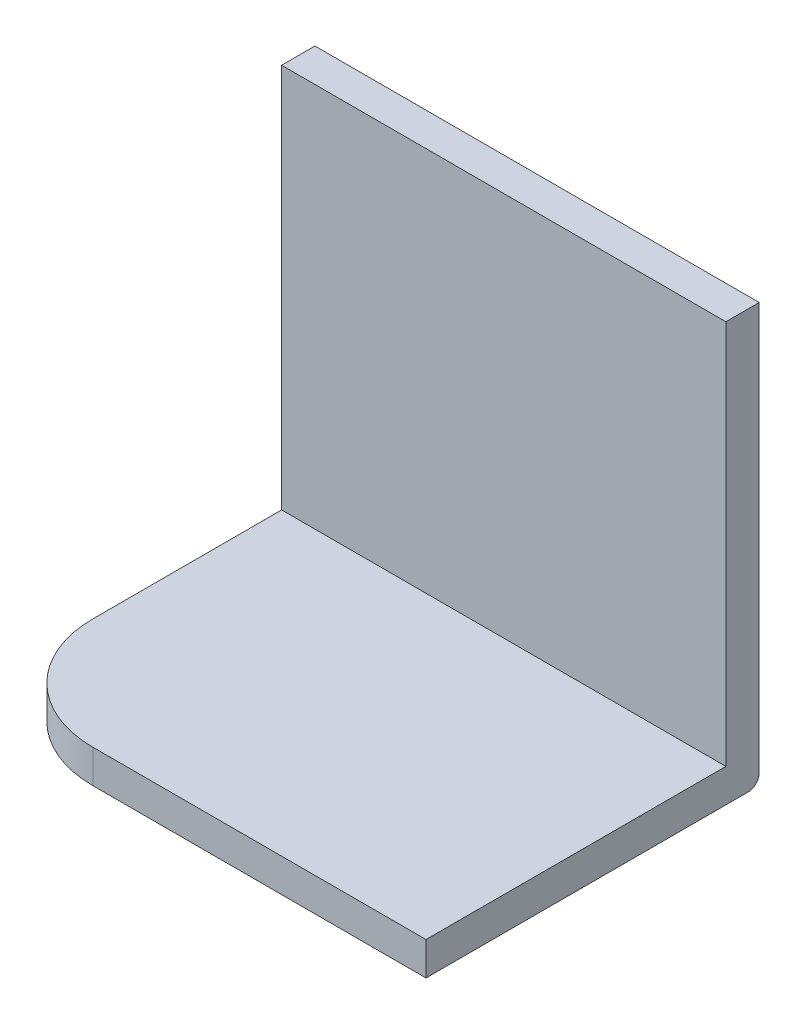
SolidWorks part; units mm, degrees
ref_plane "前视基准面" through (0, 0, 0) normal (0, 0, 1) x (1, 0, 0)
ref_plane "上视基准面" through (0, 0, 0) normal (0, 1, 0) x (1, 0, 0)
ref_plane "右视基准面" through (0, 0, 0) normal (1, 0, 0) x (0, 0, -1)
other "Configuration Table"
sketch "草图14" plane through (0, 0, 0) normal (0, 0, 1) x (1, 0, 0)
  line L0 (-20, -8.7003) -> (20, -8.7003)
  line L1 (-20, 12.5) -> (20, 12.5)
  line L2 (-20, 12.5) -> (-20, -12.5)
  line L3 (-20, -12.5) -> (20, -12.5)
  line L4 (20, 12.5) -> (20, -12.5)
  line L5 (-20, 12.5) -> (20, -12.5) construction
  line L6 (-20, -12.5) -> (20, 12.5) construction
  point P0 (0, 0)
extrude "拉伸-薄壁4" add sketch "草图14" along normal blind 30 thin contours L0
sketch "草图15" plane through (0, 0, 0) normal (1, 0, 0) x (0, 0, -1)
  line L1 (0, -8.7003) -> (-3, -8.7003)
  line L2 (0, -8.7003) -> (0, 25.9743)
  line L3 (0, 25.9743) -> (-3, 25.9743)
  line L4 (-3, -8.7003) -> (-3, 25.9743)
  dimension "D1" = 3
  dimension "D2" = 34.6746
fillet "圆角1" radius 10 1 edges at (-20, -10.2003, 30)
fillet "圆角3" radius 1 1 edges at (0, -11.7003, 0)
extrude "凸台-拉伸1" add sketch "草图15" along normal mid plane 40 contours L4 L3 L2 L1
